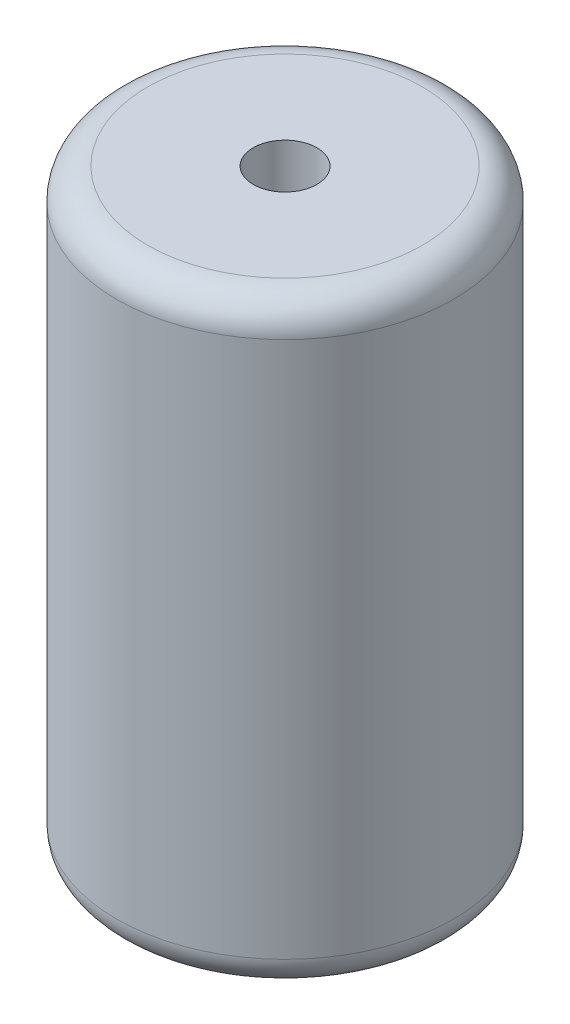
SolidWorks part; units mm, degrees
ref_plane "Alzado" through (0, 0, 0) normal (0, 0, 1) x (1, 0, 0)
ref_plane "Planta" through (0, 0, 0) normal (0, 1, 0) x (1, 0, 0)
ref_plane "Vista lateral" through (0, 0, 0) normal (1, 0, 0) x (0, 0, -1)
sketch "Croquis1" plane through (0, 0, 0) normal (0, 1, 0) x (1, 0, 0)
  circle A0 centre (0, 0) radius 27
  circle A1 centre (0, 0) radius 5.1
  dimension "D1" = 54
  dimension "D2" = 10.2
extrude "Saliente-Extruir1" add sketch "Croquis1" along normal blind 96
fillet "Redondeo1" radius 5 2 edges at (0, 0, 27) (0, 96, 27)
